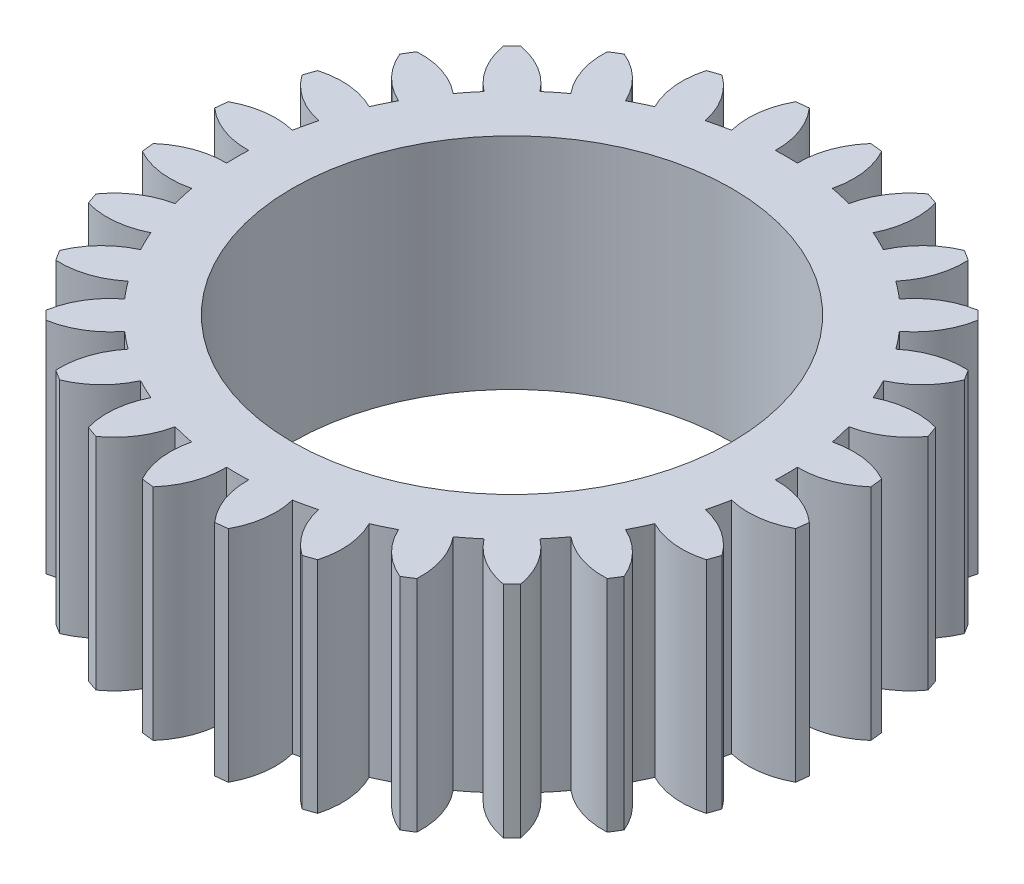
SolidWorks part; units mm, degrees
ref_plane "Front Plane" through (0, 0, 0) normal (0, 0, 1) x (1, 0, 0)
ref_plane "Top Plane" through (0, 0, 0) normal (0, 1, 0) x (1, 0, 0)
ref_plane "Right Plane" through (0, 0, 0) normal (1, 0, 0) x (0, 0, -1)
sketch "Sketch1" plane through (0, 0, 0) normal (0, 1, 0) x (1, 0, 0)
  line L0 (0, 0) -> (0, 1) construction
  line L1 (0, 1.5) -> (0, 2.7903) construction
  circle A0 centre (0, 0) radius 1
  arc A1 (0.1958, 1.4872) -> (0.14, 1.4935) centre (0, 0) ccw
  arc A2 (-0.9453, 0.8178) -> (-1.0077, 0.7396) centre (0, 0) ccw construction
  arc A3 (0.05, 1.249) -> (0.14, 1.4935) centre (0.4074, 1.2562) cw
  arc A4 (-0.05, 1.249) -> (-0.14, 1.4935) centre (-0.4074, 1.2562) ccw
  arc A5 (-0.05, 1.249) -> (0.05, 1.249) centre (0, 0) cw
  arc A6 (0.2292, 1.2288) -> (0.1958, 1.4872) centre (-0.1176, 1.3154) ccw
  arc A7 (0.3267, 1.2066) -> (0.4688, 1.4249) centre (0.6767, 1.1341) cw
  arc A8 (0.4969, 1.147) -> (0.5218, 1.4063) centre (0.178, 1.3086) ccw
  arc A9 (0.587, 1.1036) -> (0.7741, 1.2848) centre (0.9121, 0.9551) cw
  arc A10 (0.7396, 1.0077) -> (0.8217, 1.2549) centre (0.4648, 1.2361) ccw
  arc A11 (0.8178, 0.9453) -> (1.0406, 1.0803) centre (1.1017, 0.7282) cw
  arc A12 (0.9453, 0.8178) -> (1.0803, 1.0406) centre (0.7282, 1.1017) ccw
  arc A13 (1.0077, 0.7396) -> (1.2549, 0.8217) centre (1.2361, 0.4648) cw
  arc A14 (1.1036, 0.587) -> (1.2848, 0.7741) centre (0.9551, 0.9121) ccw
  arc A15 (1.147, 0.4969) -> (1.4063, 0.5218) centre (1.3086, 0.178) cw
  arc A16 (1.2066, 0.3267) -> (1.4249, 0.4688) centre (1.1341, 0.6767) ccw
  arc A17 (1.2288, 0.2292) -> (1.4872, 0.1958) centre (1.3154, -0.1176) cw
  arc A18 (1.249, 0.05) -> (1.4935, 0.14) centre (1.2562, 0.4074) ccw
  arc A19 (1.249, -0.05) -> (1.4935, -0.14) centre (1.2562, -0.4074) cw
  arc A20 (1.2288, -0.2292) -> (1.4872, -0.1958) centre (1.3154, 0.1176) ccw
  arc A21 (1.2066, -0.3267) -> (1.4249, -0.4688) centre (1.1341, -0.6767) cw
  arc A22 (1.147, -0.4969) -> (1.4063, -0.5218) centre (1.3086, -0.178) ccw
  arc A23 (1.1036, -0.587) -> (1.2848, -0.7741) centre (0.9551, -0.9121) cw
  arc A24 (1.0077, -0.7396) -> (1.2549, -0.8217) centre (1.2361, -0.4648) ccw
  arc A25 (0.9453, -0.8178) -> (1.0803, -1.0406) centre (0.7282, -1.1017) cw
  arc A26 (0.8178, -0.9453) -> (1.0406, -1.0803) centre (1.1017, -0.7282) ccw
  arc A27 (0.7396, -1.0077) -> (0.8217, -1.2549) centre (0.4648, -1.2361) cw
  arc A28 (0.587, -1.1036) -> (0.7741, -1.2848) centre (0.9121, -0.9551) ccw
  arc A29 (0.4969, -1.147) -> (0.5218, -1.4063) centre (0.178, -1.3086) cw
  arc A30 (0.3267, -1.2066) -> (0.4688, -1.4249) centre (0.6767, -1.1341) ccw
  arc A31 (0.2292, -1.2288) -> (0.1958, -1.4872) centre (-0.1176, -1.3154) cw
  arc A32 (0.05, -1.249) -> (0.14, -1.4935) centre (0.4074, -1.2562) ccw
  arc A33 (-0.05, -1.249) -> (-0.14, -1.4935) centre (-0.4074, -1.2562) cw
  arc A34 (-0.2292, -1.2288) -> (-0.1958, -1.4872) centre (0.1176, -1.3154) ccw
  arc A35 (-0.3267, -1.2066) -> (-0.4688, -1.4249) centre (-0.6767, -1.1341) cw
  arc A36 (-0.4969, -1.147) -> (-0.5218, -1.4063) centre (-0.178, -1.3086) ccw
  arc A37 (-0.587, -1.1036) -> (-0.7741, -1.2848) centre (-0.9121, -0.9551) cw
  arc A38 (-0.7396, -1.0077) -> (-0.8217, -1.2549) centre (-0.4648, -1.2361) ccw
  arc A39 (-0.8178, -0.9453) -> (-1.0406, -1.0803) centre (-1.1017, -0.7282) cw
  arc A40 (-0.9453, -0.8178) -> (-1.0803, -1.0406) centre (-0.7282, -1.1017) ccw
  arc A41 (-1.0077, -0.7396) -> (-1.2549, -0.8217) centre (-1.2361, -0.4648) cw
  arc A42 (-1.1036, -0.587) -> (-1.2848, -0.7741) centre (-0.9551, -0.9121) ccw
  arc A43 (-1.147, -0.4969) -> (-1.4063, -0.5218) centre (-1.3086, -0.178) cw
  arc A44 (-1.2066, -0.3267) -> (-1.4249, -0.4688) centre (-1.1341, -0.6767) ccw
  arc A45 (-1.2288, -0.2292) -> (-1.4872, -0.1958) centre (-1.3154, 0.1176) cw
  arc A46 (-1.249, -0.05) -> (-1.4935, -0.14) centre (-1.2562, -0.4074) ccw
  arc A47 (-1.249, 0.05) -> (-1.4935, 0.14) centre (-1.2562, 0.4074) cw
  arc A48 (-1.2288, 0.2292) -> (-1.4872, 0.1958) centre (-1.3154, -0.1176) ccw
  arc A49 (-1.2066, 0.3267) -> (-1.4249, 0.4688) centre (-1.1341, 0.6767) cw
  arc A50 (-1.147, 0.4969) -> (-1.4063, 0.5218) centre (-1.3086, 0.178) ccw
  arc A51 (-1.1036, 0.587) -> (-1.2848, 0.7741) centre (-0.9551, 0.9121) cw
  arc A52 (-1.0077, 0.7396) -> (-1.2549, 0.8217) centre (-1.2361, 0.4648) ccw
  arc A53 (-0.9453, 0.8178) -> (-1.0803, 1.0406) centre (-0.7282, 1.1017) cw
  arc A54 (-0.8178, 0.9453) -> (-1.0406, 1.0803) centre (-1.1017, 0.7282) ccw
  arc A55 (-0.7396, 1.0077) -> (-0.8217, 1.2549) centre (-0.4648, 1.2361) cw
  arc A56 (-0.587, 1.1036) -> (-0.7741, 1.2848) centre (-0.9121, 0.9551) ccw
  arc A57 (-0.4969, 1.147) -> (-0.5218, 1.4063) centre (-0.178, 1.3086) cw
  arc A58 (-0.3267, 1.2066) -> (-0.4688, 1.4249) centre (-0.6767, 1.1341) ccw
  arc A59 (-0.2292, 1.2288) -> (-0.1958, 1.4872) centre (0.1176, 1.3154) cw
  arc A60 (-0.14, 1.4935) -> (-0.1958, 1.4872) centre (0, 0) ccw
  arc A61 (-0.4688, 1.4249) -> (-0.5218, 1.4063) centre (0, 0) ccw
  arc A62 (-0.7741, 1.2848) -> (-0.8217, 1.2549) centre (0, 0) ccw
  arc A63 (-1.0406, 1.0803) -> (-1.0803, 1.0406) centre (0, 0) ccw
  arc A64 (-1.2549, 0.8217) -> (-1.2848, 0.7741) centre (0, 0) ccw
  arc A65 (-1.4063, 0.5218) -> (-1.4249, 0.4688) centre (0, 0) ccw
  arc A66 (-1.4872, 0.1958) -> (-1.4935, 0.14) centre (0, 0) ccw
  arc A67 (-1.4935, -0.14) -> (-1.4872, -0.1958) centre (0, 0) ccw
  arc A68 (-1.4249, -0.4688) -> (-1.4063, -0.5218) centre (0, 0) ccw
  arc A69 (-1.2848, -0.7741) -> (-1.2549, -0.8217) centre (0, 0) ccw
  arc A70 (-1.0803, -1.0406) -> (-1.0406, -1.0803) centre (0, 0) ccw
  arc A71 (-0.8217, -1.2549) -> (-0.7741, -1.2848) centre (0, 0) ccw
  arc A72 (-0.5218, -1.4063) -> (-0.4688, -1.4249) centre (0, 0) ccw
  arc A73 (-0.1958, -1.4872) -> (-0.14, -1.4935) centre (0, 0) ccw
  arc A74 (0.14, -1.4935) -> (0.1958, -1.4872) centre (0, 0) ccw
  arc A75 (0.4688, -1.4249) -> (0.5218, -1.4063) centre (0, 0) ccw
  arc A76 (0.7741, -1.2848) -> (0.8217, -1.2549) centre (0, 0) ccw
  arc A77 (1.0406, -1.0803) -> (1.0803, -1.0406) centre (0, 0) ccw
  arc A78 (1.2549, -0.8217) -> (1.2848, -0.7741) centre (0, 0) ccw
  arc A79 (1.4063, -0.5218) -> (1.4249, -0.4688) centre (0, 0) ccw
  arc A80 (1.4872, -0.1958) -> (1.4935, -0.14) centre (0, 0) ccw
  arc A81 (1.4935, 0.14) -> (1.4872, 0.1958) centre (0, 0) ccw
  arc A82 (1.4249, 0.4688) -> (1.4063, 0.5218) centre (0, 0) ccw
  arc A83 (1.2848, 0.7741) -> (1.2549, 0.8217) centre (0, 0) ccw
  arc A84 (1.0803, 1.0406) -> (1.0406, 1.0803) centre (0, 0) ccw
  arc A85 (0.8217, 1.2549) -> (0.7741, 1.2848) centre (0, 0) ccw
  arc A86 (0.5218, 1.4063) -> (0.4688, 1.4249) centre (0, 0) ccw
  arc A87 (-1.1036, 0.587) -> (-1.147, 0.4969) centre (0, 0) ccw construction
  arc A88 (-0.9453, 0.8178) -> (-1.0077, 0.7396) centre (0, 0) ccw
  arc A89 (-1.1036, 0.587) -> (-1.147, 0.4969) centre (0, 0) ccw
  arc A90 (-1.2066, 0.3267) -> (-1.2288, 0.2292) centre (0, 0) ccw construction
  arc A91 (-1.2066, 0.3267) -> (-1.2288, 0.2292) centre (0, 0) ccw
  arc A92 (-1.249, 0.05) -> (-1.249, -0.05) centre (0, 0) ccw construction
  arc A93 (-1.249, 0.05) -> (-1.249, -0.05) centre (0, 0) ccw
  arc A94 (-1.2288, -0.2292) -> (-1.2066, -0.3267) centre (0, 0) ccw construction
  arc A95 (-1.2288, -0.2292) -> (-1.2066, -0.3267) centre (0, 0) ccw
  arc A96 (-1.147, -0.4969) -> (-1.1036, -0.587) centre (0, 0) ccw construction
  arc A97 (-1.147, -0.4969) -> (-1.1036, -0.587) centre (0, 0) ccw
  arc A98 (-1.0077, -0.7396) -> (-0.9453, -0.8178) centre (0, 0) ccw construction
  arc A99 (-1.0077, -0.7396) -> (-0.9453, -0.8178) centre (0, 0) ccw
  arc A100 (-0.8178, -0.9453) -> (-0.7396, -1.0077) centre (0, 0) ccw construction
  arc A101 (-0.8178, -0.9453) -> (-0.7396, -1.0077) centre (0, 0) ccw
  arc A102 (-0.587, -1.1036) -> (-0.4969, -1.147) centre (0, 0) ccw construction
  arc A103 (-0.587, -1.1036) -> (-0.4969, -1.147) centre (0, 0) ccw
  arc A104 (-0.3267, -1.2066) -> (-0.2292, -1.2288) centre (0, 0) ccw construction
  arc A105 (-0.3267, -1.2066) -> (-0.2292, -1.2288) centre (0, 0) ccw
  arc A106 (-0.05, -1.249) -> (0.05, -1.249) centre (0, 0) ccw construction
  arc A107 (-0.05, -1.249) -> (0.05, -1.249) centre (0, 0) ccw
  arc A108 (0.2292, -1.2288) -> (0.3267, -1.2066) centre (0, 0) ccw construction
  arc A109 (0.2292, -1.2288) -> (0.3267, -1.2066) centre (0, 0) ccw
  arc A110 (0.4969, -1.147) -> (0.587, -1.1036) centre (0, 0) ccw construction
  arc A111 (0.4969, -1.147) -> (0.587, -1.1036) centre (0, 0) ccw
  arc A112 (0.7396, -1.0077) -> (0.8178, -0.9453) centre (0, 0) ccw construction
  arc A113 (0.7396, -1.0077) -> (0.8178, -0.9453) centre (0, 0) ccw
  arc A114 (0.9453, -0.8178) -> (1.0077, -0.7396) centre (0, 0) ccw construction
  arc A115 (0.9453, -0.8178) -> (1.0077, -0.7396) centre (0, 0) ccw
  arc A116 (1.1036, -0.587) -> (1.147, -0.4969) centre (0, 0) ccw construction
  arc A117 (1.1036, -0.587) -> (1.147, -0.4969) centre (0, 0) ccw
  arc A118 (1.2066, -0.3267) -> (1.2288, -0.2292) centre (0, 0) ccw construction
  arc A119 (1.2066, -0.3267) -> (1.2288, -0.2292) centre (0, 0) ccw
  arc A120 (1.249, -0.05) -> (1.249, 0.05) centre (0, 0) ccw construction
  arc A121 (1.249, -0.05) -> (1.249, 0.05) centre (0, 0) ccw
  arc A122 (1.2288, 0.2292) -> (1.2066, 0.3267) centre (0, 0) ccw construction
  arc A123 (1.2288, 0.2292) -> (1.2066, 0.3267) centre (0, 0) ccw
  arc A124 (1.147, 0.4969) -> (1.1036, 0.587) centre (0, 0) ccw construction
  arc A125 (1.147, 0.4969) -> (1.1036, 0.587) centre (0, 0) ccw
  arc A126 (1.0077, 0.7396) -> (0.9453, 0.8178) centre (0, 0) ccw construction
  arc A127 (1.0077, 0.7396) -> (0.9453, 0.8178) centre (0, 0) ccw
  arc A128 (0.8178, 0.9453) -> (0.7396, 1.0077) centre (0, 0) ccw construction
  arc A129 (0.8178, 0.9453) -> (0.7396, 1.0077) centre (0, 0) ccw
  arc A130 (0.587, 1.1036) -> (0.4969, 1.147) centre (0, 0) ccw construction
  arc A131 (0.587, 1.1036) -> (0.4969, 1.147) centre (0, 0) ccw
  arc A132 (-0.7396, 1.0077) -> (-0.8178, 0.9453) centre (0, 0) ccw construction
  arc A133 (-0.7396, 1.0077) -> (-0.8178, 0.9453) centre (0, 0) ccw
  arc A134 (-0.4969, 1.147) -> (-0.587, 1.1036) centre (0, 0) ccw construction
  arc A135 (-0.4969, 1.147) -> (-0.587, 1.1036) centre (0, 0) ccw
  arc A136 (-0.2292, 1.2288) -> (-0.3267, 1.2066) centre (0, 0) ccw construction
  arc A137 (-0.2292, 1.2288) -> (-0.3267, 1.2066) centre (0, 0) ccw
  arc A138 (0.05, 1.249) -> (-0.05, 1.249) centre (0, 0) ccw construction
  arc A139 (0.05, 1.249) -> (-0.05, 1.249) centre (0, 0) ccw
  arc A140 (0.3267, 1.2066) -> (0.2292, 1.2288) centre (0, 0) ccw construction
  arc A141 (0.3267, 1.2066) -> (0.2292, 1.2288) centre (0, 0) ccw
  point P159 (0, 0)
  dimension "D1" = 2
  dimension "D2" = 3
  dimension "D3" = 2.5
  dimension "D8" = 1.25
  dimension "D4" = 0.05
  dimension "D5" = 0.14
  dimension "D7" = 0.2445
  dimension "D6" = 28
extrude "Boss-Extrude1" add sketch "Sketch1" along normal blind 1 contours A7 A141 A6 A1 A3 A5 A4 A60 A59 A137 A58 A61 A57 A135 A56 A62 A55 A133 A54 A63 A53 A88 A52 A64 A51 A89 A50 A65 A49 A91 A48 A66 A47 A93 A46 A67 A45 A95 A44 A68 A43 A97 A42 A69 A41 A99 A40 A70 A39 A101 A38 | A0
